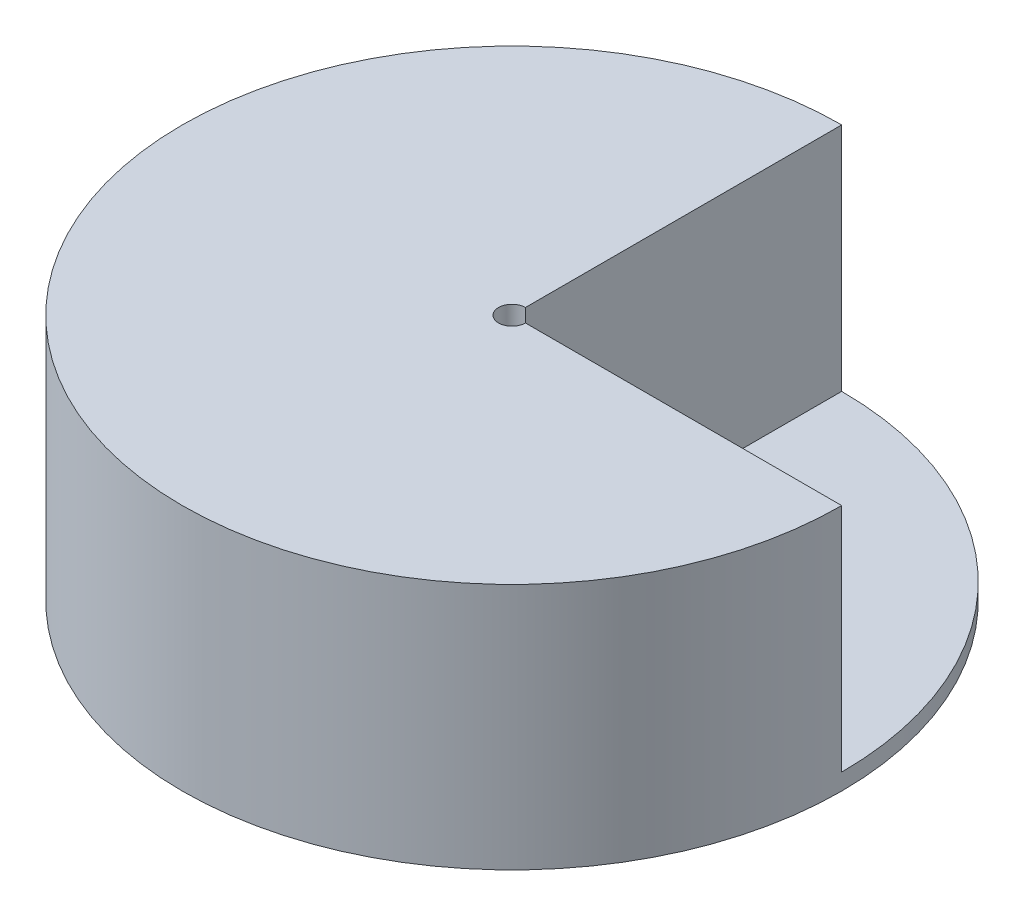
SolidWorks part; units mm, degrees
ref_plane "Front Plane" through (0, 0, 0) normal (0, 0, 1) x (1, 0, 0)
ref_plane "Top Plane" through (0, 0, 0) normal (0, 1, 0) x (1, 0, 0)
ref_plane "Right Plane" through (0, 0, 0) normal (1, 0, 0) x (0, 0, -1)
sketch "Sketch5" plane through (0, 0, 0) normal (0, 1, 0) x (1, 0, 0)
  circle A0 centre (0, 0) radius 20
  dimension "D1" = 40
extrude "Boss-Extrude2" add sketch "Sketch5" along normal blind 15
sketch "Sketch6" plane through (0, 15, 0) normal (0, 1, 0) x (1, 0, 0)
  line L0 (0, 20) -> (0, 0)
  line L1 (0, 0) -> (20, 0)
  circle A0 centre (0, 0) radius 20 construction
  arc A1 (20, 0) -> (0, 20) centre (0, 0) ccw
extrude "Cut-Extrude1" cut sketch "Sketch6" against normal blind 14
sketch "Sketch7" plane through (0, 15, 0) normal (0, 1, 0) x (1, 0, 0)
  circle A0 centre (0, 0) radius 0.815
  dimension "D1" = 1.63
extrude "Cut-Extrude2" cut sketch "Sketch7" against normal blind 150
